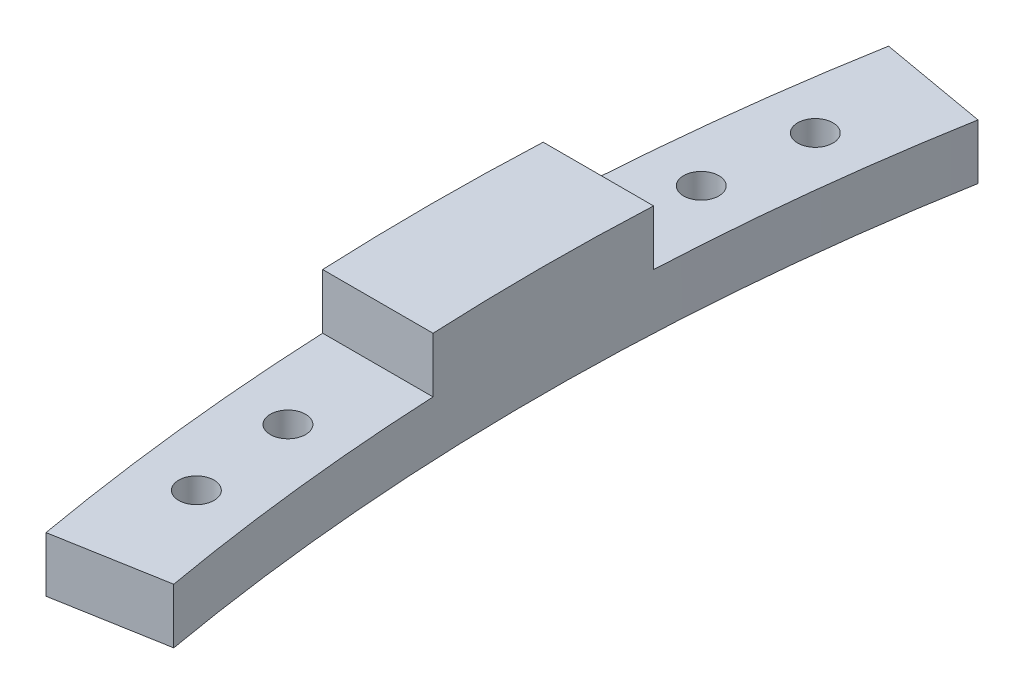
SolidWorks part; units mm, degrees
ref_plane "Front Plane" through (0, 0, 0) normal (0, 0, 1) x (1, 0, 0)
ref_plane "Top Plane" through (0, 0, 0) normal (0, 1, 0) x (1, 0, 0)
ref_plane "Right Plane" through (0, 0, 0) normal (1, 0, 0) x (0, 0, -1)
sketch "Sketch1" plane through (0, 0, 0) normal (0, 1, 0) x (1, 0, 0)
  line L0 (0, 0) -> (-216.6577, -38.2026) construction
  line L1 (0, 0) -> (-216.6577, 38.2026) construction
  line L2 (0, 0) -> (-215, 0) construction
  line L3 (-216.6577, 38.2026) -> (-206.8096, 36.4661)
  line L4 (-206.8096, -36.4661) -> (-216.6577, -38.2026)
  arc A0 (-216.6577, 38.2026) -> (-216.6577, -38.2026) centre (0, 0) ccw
  arc A1 (-206.8096, 36.4661) -> (-206.8096, -36.4661) centre (0, 0) ccw
  arc A2 (-211.7337, -37.3344) -> (-211.7337, 37.3344) centre (0, 0) cw construction
  point P8 (-217.7665, -38.2026)
  point P9 (-208.2477, 36.4661)
  point P10 (-205.4466, -36.4661)
  point P11 (-217.8762, 38.2026)
  dimension "D1" = 220
  dimension "D2" = 210
  dimension "D3" = 5
  dimension "D4" = 20
extrude "Boss-Extrude1" add sketch "Sketch1" along normal blind 5
sketch "Sketch2" [suppressed] plane through (0, 7.5, 0) normal (0, 1, 0) x (1, 0, 0)
  line L2 (0, 0) -> (-215, 0) construction
  line L3 (0, 0) -> (-219.1197, -38.6367) construction
  line L4 (0, 0) -> (-219.1197, 38.6367) construction
  line L5 (0, 0) -> (-210, 0) construction
  line L6 (0, 0) -> (-219.1197, -38.6367) construction
  line L7 (0, 0) -> (-219.1197, 38.6367) construction
  line L8 (0, 10) -> (-222.2752, 10) construction
  line L9 (0, 10) -> (0, -10) construction
  line L10 (0, -10) -> (-222.2752, -10) construction
  line L11 (-216.6577, 38.2026) -> (-206.8096, 36.4661)
  line L12 (-216.6577, -38.2026) -> (-206.8096, -36.4661)
  line L13 (-219.7726, -10) -> (-209.7618, -10)
  line L14 (-209.7618, 10) -> (-219.7726, 10)
  arc A0 (-216.6577, 38.2026) -> (-216.6577, -38.2026) centre (0, 0) ccw construction
  arc A1 (-206.8096, 36.4661) -> (-206.8096, -36.4661) centre (0, 0) ccw construction
  arc A2 (-216.6577, 38.2026) -> (-216.6577, -38.2026) centre (0, 0) ccw
  arc A3 (-206.8096, 36.4661) -> (-206.8096, -36.4661) centre (0, 0) ccw
  arc A4 (-219.1197, 38.6367) -> (-219.1197, -38.6367) centre (0, 0) ccw construction
  line M2 (-219.1197, -38.6367) -> (-204.3476, -36.032)
  line M4 (-204.3476, 36.032) -> (-219.1197, 38.6367)
  dimension "D1" = 20
extrude "Cut-Extrude1" [suppressed] cut sketch "Sketch2" against normal blind 1.5 contours A3 A2 L14 M4 | A3 L13 A2 M2
ref_plane "Plane1" through (-215, 0, 0) normal (1, 0, 0) x (0, 0, -1)
sketch "Sketch6" plane through (0, 0, 0) normal (0, -1, 0) x (1, 0, 0)
  line L0 (0, 0) -> (-214.1819, 18.7385) construction
  line L1 (0, 0) -> (-215, 0) construction
  line L2 (0, 0) -> (-215, 0) construction
  line L3 (0, 0) -> (-214.1819, -18.7385) construction
  line L4 (0, 0) -> (-213.1606, 28.0631) construction
  line L5 (0, 0) -> (-213.1606, -28.0631) construction
  arc A0 (-211.7337, 37.3344) -> (-211.7337, -37.3344) centre (0, 0) ccw construction
  dimension "D1" = 5
  dimension "D2" = 7.5
hole_wizard "Ø3.2 (3.2) Diameter Hole1" positions "Sketch7" profile "Sketch8" hole size "Ø3.2" standard "ISO" end condition through all
sketch "Sketch7" plane through (0, 0, 0) normal (0, -1, 0) x (-1, 0, 0)
  point P0 (214.1819, -18.7385)
  point P3 (214.1819, 18.7385)
  point P6 (213.1606, -28.0631)
  point P9 (213.1606, 28.0631)
sketch "Sketch8" plane through (-214.1819, 0, 18.7385) normal (1, 0, 0) x (0, 0, -1)
  line L0 (0, 0) -> (0, 5)
  line L1 (0, 5) -> (1.6, 5)
  line L2 (1.6, 5) -> (1.6, 0)
  line L5 (1.6, 0) -> (0, 0)
  line L11 (0, -6.35) -> (0, 107.95) construction
  dimension "Thru Hole Dia." = 3.2
  dimension "Thru Hole Depth" = 5
sketch "Sketch9" plane through (0, 5, 0) normal (0, 1, 0) x (1, 0, 0)
  line L0 (0, 0) -> (-215, 0) construction
  line L1 (0, 0) -> (-215, 0) construction
  line L2 (0, 10) -> (0, -10) construction
  line L3 (-219.7726, 10) -> (-209.7618, 10)
  line L4 (-219.7726, -10) -> (-209.7618, -10)
  arc A0 (-216.6577, 38.2026) -> (-216.6577, -38.2026) centre (0, 0) ccw construction
  arc A1 (-206.8096, 36.4661) -> (-206.8096, -36.4661) centre (0, 0) ccw construction
  arc A2 (-209.7618, 10) -> (-209.7618, -10) centre (0, 0) ccw
  arc A3 (-219.7726, 10) -> (-219.7726, -10) centre (0, 0) ccw
  point P2 (-215, 0)
  point P10 (0, 12.2622)
  point P13 (0, -12.1892)
  dimension "D1" = 20
extrude "Boss-Extrude2" add sketch "Sketch9" along normal blind 5
